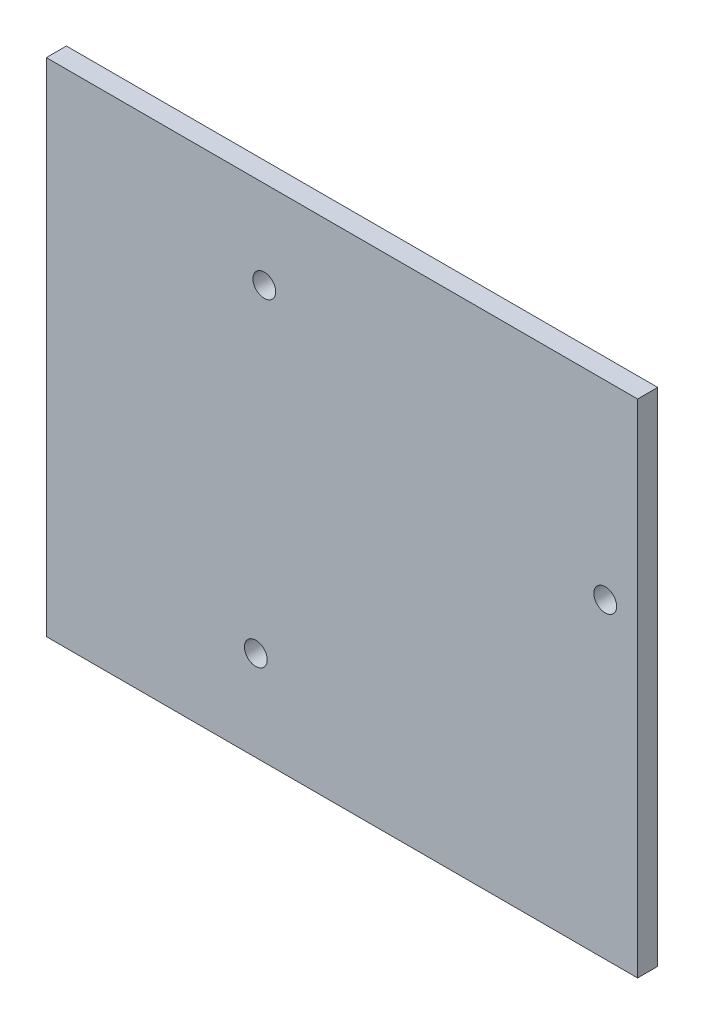
SolidWorks part; units mm, degrees
ref_plane "Plan de face" through (0, 0, 0) normal (0, 0, 1) x (1, 0, 0)
ref_plane "Plan de dessus" through (0, 0, 0) normal (0, 1, 0) x (1, 0, 0)
ref_plane "Plan de droite" through (0, 0, 0) normal (1, 0, 0) x (0, 0, -1)
sketch "Esquisse1" plane through (0, 0, 0) normal (0, 0, 1) x (1, 0, 0)
  line L0 (-26.095, -24.13) -> (26.095, 8.89) construction
  line L1 (-26.095, 24.13) -> (26.095, 24.13) construction
  line L2 (-26.095, 24.13) -> (-26.095, -24.13) construction
  line L3 (-26.095, -24.13) -> (26.095, -24.13) construction
  line L4 (26.095, 24.13) -> (26.095, -24.13) construction
  line L5 (-26.095, 24.13) -> (26.095, -24.13) construction
  line L6 (-26.095, -24.13) -> (26.095, 24.13) construction
  line L7 (26.095, 8.89) -> (-24.825, 24.13) construction
  line L8 (-24.825, 24.13) -> (-26.095, -24.13) construction
  line L10 (30.9366, -37.6116) -> (-57.392, -37.6116)
  line L11 (30.9366, -37.6116) -> (30.9366, 37.2919)
  line L12 (30.9366, 37.2919) -> (-57.392, 37.2919)
  line L13 (-57.392, -37.6116) -> (-57.392, 37.2919)
  point P0 (0, 0)
  dimension "D1" = 52.19
  dimension "D2" = 48.26
  dimension "D3" = 15.24
  dimension "D4" = 1.27
extrude "Boss.-Extru.1" add sketch "Esquisse1" against normal blind 3
hole_wizard "Dégagement M31" positions "Esquisse4" profile "Esquisse5" hole size "M3" standard "ISO" end condition up to next
sketch "Esquisse4" plane through (0, 0, 0) normal (0, 0, 1) x (1, 0, 0)
  point P0 (26.095, 8.89)
  point P3 (-24.825, 24.13)
  point P6 (-26.095, -24.13)
sketch "Esquisse5" plane through (26.095, 8.89, 0) normal (1, 0, 0) x (0, -1, 0)
  line L0 (0, 0) -> (0, 3)
  line L1 (0, 3) -> (1.7, 3)
  line L2 (1.7, 3) -> (1.7, 0)
  line L5 (1.7, 0) -> (0, 0)
  line L11 (0, -6.35) -> (0, 107.95) construction
  dimension "Diamètre du perçage jusqu'au prochain" = 3.4
  dimension "Profondeur du perçage jusqu'au prochain" = 3
